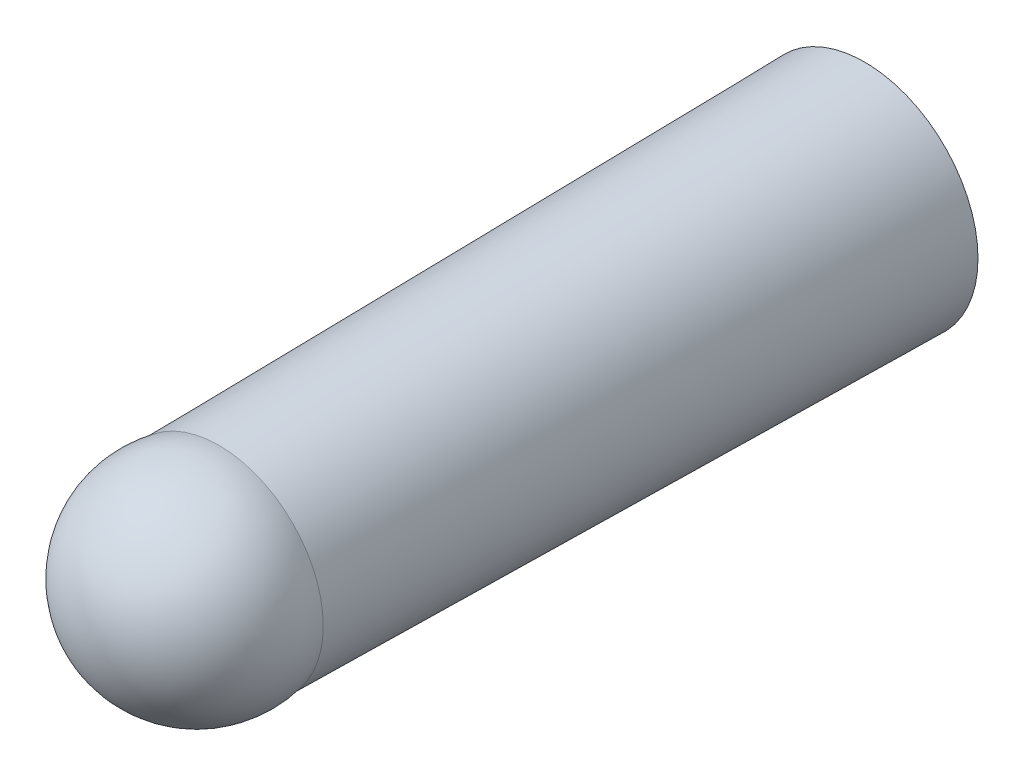
SolidWorks part; units mm, degrees
ref_plane "Front Plane" through (0, 0, 0) normal (0, 0, 1) x (1, 0, 0)
ref_plane "Top Plane" through (0, 0, 0) normal (0, 1, 0) x (1, 0, 0)
ref_plane "Right Plane" through (0, 0, 0) normal (1, 0, 0) x (0, 0, -1)
sketch "Sketch1" plane through (0, 0, 0) normal (0, 0, 1) x (1, 0, 0)
  circle A0 centre (0, 0) radius 47.5
  dimension "D1" = 95
extrude "Boss-Extrude1" add sketch "Sketch1" along normal blind 280 draft 0.8
sketch "Sketch2" plane through (0, 0, 0) normal (0, 0, -1) x (-1, 0, 0)
  line L0 (0, 42.5) -> (0, -42.5)
  arc A0 (0, -42.5) -> (0, 42.5) centre (0, 0) ccw
  dimension "D1" = 85
revolve "Cut-Revolve2" cut sketch "Sketch2" angle 360 about L0
sketch "Sketch3" plane through (0, 0, 280) normal (0, 0, 1) x (1, 0, 0)
  line L0 (0, 44.7073) -> (0, -44.7073)
  arc A0 (0, 44.7073) -> (0, -44.7073) centre (0, 0) ccw
revolve "Revolve1" add sketch "Sketch3" angle 360 about L0
